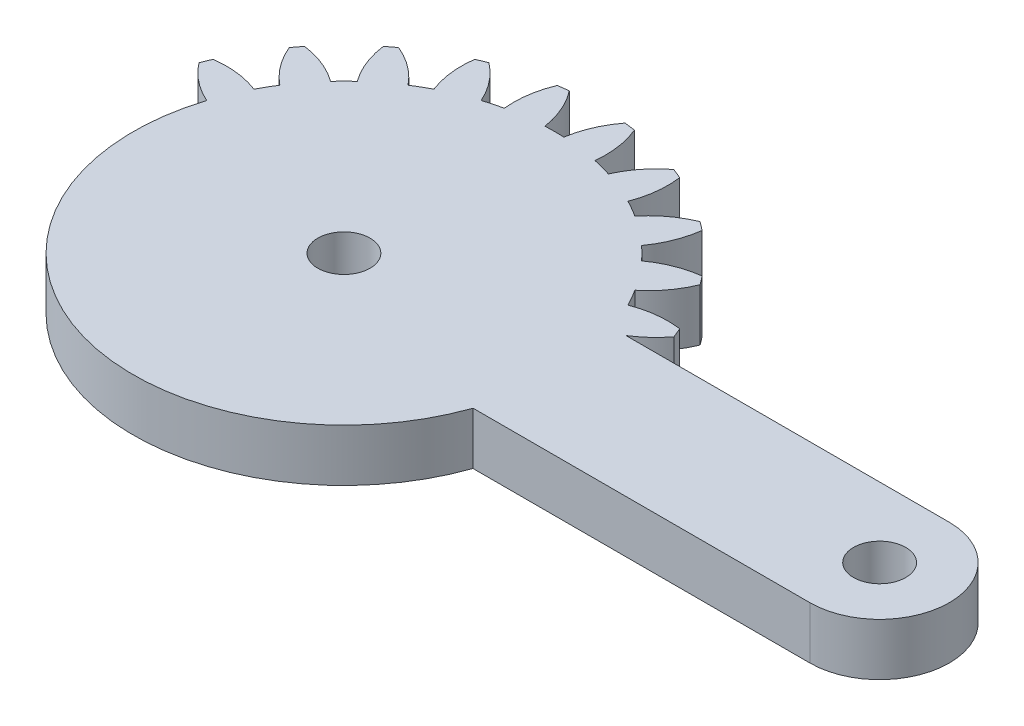
SolidWorks part; units mm, degrees
ref_plane "Front Plane" through (0, 0, 0) normal (0, 0, 1) x (1, 0, 0)
ref_plane "Top Plane" through (0, 0, 0) normal (0, 1, 0) x (1, 0, 0)
ref_plane "Right Plane" through (0, 0, 0) normal (1, 0, 0) x (0, 0, -1)
sketch "Sketch1" plane through (0, 0, 0) normal (0, 1, 0) x (1, 0, 0)
  line L0 (20.6437, 4) -> (2.0816, 4)
  line L1 (2.0816, -4) -> (20.6437, -4)
  arc A0 (2.0816, 4) -> (3.5217, 5.3071) centre (-0.7683, 8.5867) ccw
  arc A1 (3.5217, 5.3071) -> (3.2829, 5.8838) centre (-10.1063, 0) ccw
  arc A2 (3.2829, 5.8838) -> (0.6271, 5.5703) centre (2.5684, 0.5313) ccw
  arc A3 (0.6271, 5.5703) -> (0.0844, 6.5103) centre (-10.1063, 0) ccw
  arc A4 (0.0844, 6.5103) -> (1.6838, 8.6535) centre (-3.3089, 10.711) ccw
  arc A5 (1.6838, 8.6535) -> (1.3038, 9.1487) centre (-10.1063, 0) ccw
  arc A6 (1.3038, 9.1487) -> (-1.1803, 8.1585) centre (1.999, 3.7936) ccw
  arc A7 (-1.1803, 8.1585) -> (-1.9479, 8.926) centre (-10.1063, 0) ccw
  arc A8 (-1.9479, 8.926) -> (-0.9576, 11.4102) centre (-6.3127, 12.1053) ccw
  arc A9 (-0.9576, 11.4102) -> (-1.4528, 11.7901) centre (-10.1063, 0) ccw
  arc A10 (-1.4528, 11.7901) -> (-3.596, 10.1907) centre (0.6046, 6.7975) ccw
  arc A11 (-3.596, 10.1907) -> (-4.5361, 10.7334) centre (-10.1063, 0) ccw
  arc A12 (-4.5361, 10.7334) -> (-4.2225, 13.3892) centre (-9.5751, 12.6747) ccw
  arc A13 (-4.2225, 13.3892) -> (-4.7992, 13.6281) centre (-10.1063, 0) ccw
  arc A14 (-4.7992, 13.6281) -> (-6.4554, 11.5285) centre (-1.5196, 9.3381) ccw
  arc A15 (-6.4554, 11.5285) -> (-7.5039, 11.8094) centre (-10.1063, 0) ccw
  arc A16 (-7.5039, 11.8094) -> (-7.8884, 14.4558) centre (-12.8736, 12.3803) ccw
  arc A17 (-7.8884, 14.4558) -> (-8.5072, 14.5373) centre (-10.1063, 0) ccw
  arc A18 (-8.5072, 14.5373) -> (-9.5636, 12.0806) centre (-4.2291, 11.2423) ccw
  arc A19 (-9.5636, 12.0806) -> (-10.6491, 12.0806) centre (-10.1063, 0) ccw
  arc A20 (-10.6491, 12.0806) -> (-11.7054, 14.5373) centre (-15.9836, 11.2423) ccw
  arc A21 (-11.7054, 14.5373) -> (-12.3243, 14.4558) centre (-10.1063, 0) ccw
  arc A22 (-12.3243, 14.4558) -> (-12.7088, 11.8094) centre (-7.3391, 12.3803) ccw
  arc A23 (-12.7088, 11.8094) -> (-13.7573, 11.5285) centre (-10.1063, 0) ccw
  arc A24 (-13.7573, 11.5285) -> (-15.4135, 13.6281) centre (-18.6931, 9.3381) ccw
  arc A25 (-15.4135, 13.6281) -> (-15.9901, 13.3892) centre (-10.1063, 0) ccw
  arc A26 (-15.9901, 13.3892) -> (-15.6766, 10.7334) centre (-10.6376, 12.6747) ccw
  arc A27 (-15.6766, 10.7334) -> (-16.6166, 10.1907) centre (-10.1063, 0) ccw
  arc A28 (-16.6166, 10.1907) -> (-18.7599, 11.7901) centre (-20.8173, 6.7975) ccw
  arc A29 (-18.7599, 11.7901) -> (-19.255, 11.4102) centre (-10.1063, 0) ccw
  arc A30 (-19.255, 11.4102) -> (-18.2648, 8.926) centre (-13.9, 12.1053) ccw
  arc A31 (-18.2648, 8.926) -> (-19.0324, 8.1585) centre (-10.1063, 0) ccw
  arc A32 (-19.0324, 8.1585) -> (-21.5165, 9.1487) centre (-22.2117, 3.7936) ccw
  arc A33 (-21.5165, 9.1487) -> (-21.8965, 8.6535) centre (-10.1063, 0) ccw
  arc A34 (-21.8965, 8.6535) -> (-20.2971, 6.5103) centre (-16.9038, 10.711) ccw
  arc A35 (-20.2971, 6.5103) -> (-20.8398, 5.5703) centre (-10.1063, 0) ccw
  arc A36 (-20.8398, 5.5703) -> (-23.4956, 5.8838) centre (-22.7811, 0.5313) ccw
  arc A37 (-23.4956, 5.8838) -> (-23.7344, 5.3071) centre (-10.1063, 0) ccw
  arc A38 (-23.7344, 5.3071) -> (-21.6348, 3.6509) centre (-19.4444, 8.5867) ccw
  arc A39 (-21.6348, 3.6509) -> (-21.9157, 2.6025) centre (-10.1063, 0) ccw
  arc A40 (-21.9157, 2.6025) -> (-24.5622, 2.2179) centre (-22.4867, -2.7673) ccw
  arc A41 (-24.5622, 2.2179) -> (-24.6437, 1.5991) centre (-10.1063, 0) ccw
  arc A42 (-24.6437, 1.5991) -> (-22.1869, 0.5427) centre (-21.3486, 5.8773) ccw
  arc A43 (-22.1869, 0.5427) -> (-22.1869, -0.5427) centre (-10.1063, 0) ccw
  arc A44 (-22.1869, -0.5427) -> (-24.6437, -1.5991) centre (-21.3486, -5.8773) ccw
  arc A45 (-24.6437, -1.5991) -> (-24.5622, -2.2179) centre (-10.1063, 0) ccw
  arc A46 (-24.5622, -2.2179) -> (-21.9157, -2.6025) centre (-22.4867, 2.7673) ccw
  arc A47 (-21.9157, -2.6025) -> (-21.6348, -3.6509) centre (-10.1063, 0) ccw
  arc A48 (-21.6348, -3.6509) -> (-23.7344, -5.3071) centre (-19.4444, -8.5867) ccw
  arc A49 (-23.7344, -5.3071) -> (-23.4956, -5.8838) centre (-10.1063, 0) ccw
  arc A50 (-23.4956, -5.8838) -> (-20.8398, -5.5703) centre (-22.7811, -0.5313) ccw
  arc A51 (-20.8398, -5.5703) -> (-20.2971, -6.5103) centre (-10.1063, 0) ccw
  arc A52 (-20.2971, -6.5103) -> (-21.8965, -8.6535) centre (-16.9038, -10.711) ccw
  arc A53 (-21.8965, -8.6535) -> (-21.5165, -9.1487) centre (-10.1063, 0) ccw
  arc A54 (-21.5165, -9.1487) -> (-19.0324, -8.1585) centre (-22.2117, -3.7936) ccw
  arc A55 (-19.0324, -8.1585) -> (-18.2648, -8.926) centre (-10.1063, 0) ccw
  arc A56 (-18.2648, -8.926) -> (-19.255, -11.4102) centre (-13.9, -12.1053) ccw
  arc A57 (-19.255, -11.4102) -> (-18.7599, -11.7901) centre (-10.1063, 0) ccw
  arc A58 (-18.7599, -11.7901) -> (-16.6166, -10.1907) centre (-20.8173, -6.7975) ccw
  arc A59 (-16.6166, -10.1907) -> (-15.6766, -10.7334) centre (-10.1063, 0) ccw
  arc A60 (-15.6766, -10.7334) -> (-15.9901, -13.3892) centre (-10.6376, -12.6747) ccw
  arc A61 (-15.9901, -13.3892) -> (-15.4135, -13.6281) centre (-10.1063, 0) ccw
  arc A62 (-15.4135, -13.6281) -> (-13.7573, -11.5285) centre (-18.6931, -9.3381) ccw
  arc A63 (-13.7573, -11.5285) -> (-12.7088, -11.8094) centre (-10.1063, 0) ccw
  arc A64 (-12.7088, -11.8094) -> (-12.3243, -14.4558) centre (-7.3391, -12.3803) ccw
  arc A65 (-12.3243, -14.4558) -> (-11.7054, -14.5373) centre (-10.1063, 0) ccw
  arc A66 (-11.7054, -14.5373) -> (-10.6491, -12.0806) centre (-15.9836, -11.2423) ccw
  arc A67 (-10.6491, -12.0806) -> (-9.5636, -12.0806) centre (-10.1063, 0) ccw
  arc A68 (-9.5636, -12.0806) -> (-8.5072, -14.5373) centre (-4.2291, -11.2423) ccw
  arc A69 (-8.5072, -14.5373) -> (-7.8884, -14.4558) centre (-10.1063, 0) ccw
  arc A70 (-7.8884, -14.4558) -> (-7.5039, -11.8094) centre (-12.8736, -12.3803) ccw
  arc A71 (-7.5039, -11.8094) -> (-6.4554, -11.5285) centre (-10.1063, 0) ccw
  arc A72 (-6.4554, -11.5285) -> (-4.7992, -13.6281) centre (-1.5196, -9.3381) ccw
  arc A73 (-4.7992, -13.6281) -> (-4.2225, -13.3892) centre (-10.1063, 0) ccw
  arc A74 (-4.2225, -13.3892) -> (-4.5361, -10.7334) centre (-9.5751, -12.6747) ccw
  arc A75 (-4.5361, -10.7334) -> (-3.596, -10.1907) centre (-10.1063, 0) ccw
  arc A76 (-3.596, -10.1907) -> (-1.4528, -11.7901) centre (0.6046, -6.7975) ccw
  arc A77 (-1.4528, -11.7901) -> (-0.9576, -11.4102) centre (-10.1063, 0) ccw
  arc A78 (-0.9576, -11.4102) -> (-1.9479, -8.926) centre (-6.3127, -12.1053) ccw
  arc A79 (-1.9479, -8.926) -> (-1.1803, -8.1585) centre (-10.1063, 0) ccw
  arc A80 (-1.1803, -8.1585) -> (1.3038, -9.1487) centre (1.999, -3.7936) ccw
  arc A81 (1.3038, -9.1487) -> (1.6838, -8.6535) centre (-10.1063, 0) ccw
  arc A82 (1.6838, -8.6535) -> (0.0844, -6.5103) centre (-3.3089, -10.711) ccw
  arc A83 (0.0844, -6.5103) -> (0.6271, -5.5703) centre (-10.1063, 0) ccw
  arc A84 (0.6271, -5.5703) -> (3.2829, -5.8838) centre (2.5684, -0.5313) ccw
  arc A85 (3.2829, -5.8838) -> (3.5217, -5.3071) centre (-10.1063, 0) ccw
  arc A86 (3.5217, -5.3071) -> (2.0816, -4) centre (-0.7683, -8.5867) ccw
  arc A87 (20.6437, -4) -> (20.6437, 4) centre (20.6437, 0) ccw
  circle A88 centre (-10.1063, 0) radius 1.5
  circle A89 centre (20.6437, 0) radius 1.5
  dimension "D1" = 3
  dimension "D2" = 3
extrude "Boss-Extrude1" add sketch "Sketch1" along normal blind 3
sketch "Sketch2" plane through (0, 3, 0) normal (0, 1, 0) x (1, 0, 0)
  line L0 (2.0816, -4) -> (1.3057, -4)
  line L2 (20.6437, 4) -> (2.0816, 4)
  line L3 (2.0816, -4) -> (20.6437, -4)
  line L4 (20.6437, 4) -> (2.0816, 4)
  line L5 (2.0816, -4) -> (20.6437, -4)
  circle A0 centre (-10.1063, 0) radius 12.0927
  arc A88 (20.6437, -4) -> (20.6437, 4) centre (20.6437, 0) ccw
  arc A89 (2.0816, 4) -> (3.5217, 5.3071) centre (-0.7683, 8.5867) ccw
  arc A90 (3.5217, 5.3071) -> (3.2829, 5.8838) centre (-10.1063, 0) ccw
  arc A91 (3.2829, 5.8838) -> (0.6271, 5.5703) centre (2.5684, 0.5313) ccw
  arc A92 (0.6271, 5.5703) -> (0.0844, 6.5103) centre (-10.1063, 0) ccw
  arc A93 (0.0844, 6.5103) -> (1.6838, 8.6535) centre (-3.3089, 10.711) ccw
  arc A94 (1.6838, 8.6535) -> (1.3038, 9.1487) centre (-10.1063, 0) ccw
  arc A95 (1.3038, 9.1487) -> (-1.1803, 8.1585) centre (1.999, 3.7936) ccw
  arc A96 (-1.1803, 8.1585) -> (-1.9479, 8.926) centre (-10.1063, 0) ccw
  arc A97 (-1.9479, 8.926) -> (-0.9576, 11.4102) centre (-6.3127, 12.1053) ccw
  arc A98 (-0.9576, 11.4102) -> (-1.4528, 11.7901) centre (-10.1063, 0) ccw
  arc A99 (-1.4528, 11.7901) -> (-3.596, 10.1907) centre (0.6046, 6.7975) ccw
  arc A100 (-3.596, 10.1907) -> (-4.5361, 10.7334) centre (-10.1063, 0) ccw
  arc A101 (-4.5361, 10.7334) -> (-4.2225, 13.3892) centre (-9.5751, 12.6747) ccw
  arc A102 (-4.2225, 13.3892) -> (-4.7992, 13.6281) centre (-10.1063, 0) ccw
  arc A103 (-4.7992, 13.6281) -> (-6.4554, 11.5285) centre (-1.5196, 9.3381) ccw
  arc A104 (-6.4554, 11.5285) -> (-7.5039, 11.8094) centre (-10.1063, 0) ccw
  arc A105 (-7.5039, 11.8094) -> (-7.8884, 14.4558) centre (-12.8736, 12.3803) ccw
  arc A106 (-7.8884, 14.4558) -> (-8.5072, 14.5373) centre (-10.1063, 0) ccw
  arc A107 (-8.5072, 14.5373) -> (-9.5636, 12.0806) centre (-4.2291, 11.2423) ccw
  arc A108 (-9.5636, 12.0806) -> (-10.6491, 12.0806) centre (-10.1063, 0) ccw
  arc A109 (-10.6491, 12.0806) -> (-11.7054, 14.5373) centre (-15.9836, 11.2423) ccw
  arc A110 (-11.7054, 14.5373) -> (-12.3243, 14.4558) centre (-10.1063, 0) ccw
  arc A111 (-12.3243, 14.4558) -> (-12.7088, 11.8094) centre (-7.3391, 12.3803) ccw
  arc A112 (-12.7088, 11.8094) -> (-13.7573, 11.5285) centre (-10.1063, 0) ccw
  arc A113 (-13.7573, 11.5285) -> (-15.4135, 13.6281) centre (-18.6931, 9.3381) ccw
  arc A114 (-15.4135, 13.6281) -> (-15.9901, 13.3892) centre (-10.1063, 0) ccw
  arc A115 (-15.9901, 13.3892) -> (-15.6766, 10.7334) centre (-10.6376, 12.6747) ccw
  arc A116 (-15.6766, 10.7334) -> (-16.6166, 10.1907) centre (-10.1063, 0) ccw
  arc A117 (-16.6166, 10.1907) -> (-18.7599, 11.7901) centre (-20.8173, 6.7975) ccw
  arc A118 (-18.7599, 11.7901) -> (-19.255, 11.4102) centre (-10.1063, 0) ccw
  arc A119 (-19.255, 11.4102) -> (-18.2648, 8.926) centre (-13.9, 12.1053) ccw
  arc A120 (-18.2648, 8.926) -> (-19.0324, 8.1585) centre (-10.1063, 0) ccw
  arc A121 (-19.0324, 8.1585) -> (-21.5165, 9.1487) centre (-22.2117, 3.7936) ccw
  arc A122 (-21.5165, 9.1487) -> (-21.8965, 8.6535) centre (-10.1063, 0) ccw
  arc A123 (-21.8965, 8.6535) -> (-20.2971, 6.5103) centre (-16.9038, 10.711) ccw
  arc A124 (-20.2971, 6.5103) -> (-20.8398, 5.5703) centre (-10.1063, 0) ccw
  arc A125 (-20.8398, 5.5703) -> (-23.4956, 5.8838) centre (-22.7811, 0.5313) ccw
  arc A126 (-23.4956, 5.8838) -> (-23.7344, 5.3071) centre (-10.1063, 0) ccw
  arc A127 (-23.7344, 5.3071) -> (-21.6348, 3.6509) centre (-19.4444, 8.5867) ccw
  arc A128 (-21.6348, 3.6509) -> (-21.9157, 2.6025) centre (-10.1063, 0) ccw
  arc A129 (-21.9157, 2.6025) -> (-24.5622, 2.2179) centre (-22.4867, -2.7673) ccw
  arc A130 (-24.5622, 2.2179) -> (-24.6437, 1.5991) centre (-10.1063, 0) ccw
  arc A131 (-24.6437, 1.5991) -> (-22.1869, 0.5427) centre (-21.3486, 5.8773) ccw
  arc A132 (-22.1869, 0.5427) -> (-22.1869, -0.5427) centre (-10.1063, 0) ccw
  arc A133 (-22.1869, -0.5427) -> (-24.6437, -1.5991) centre (-21.3486, -5.8773) ccw
  arc A134 (-24.6437, -1.5991) -> (-24.5622, -2.2179) centre (-10.1063, 0) ccw
  arc A135 (-24.5622, -2.2179) -> (-21.9157, -2.6025) centre (-22.4867, 2.7673) ccw
  arc A136 (-21.9157, -2.6025) -> (-21.6348, -3.6509) centre (-10.1063, 0) ccw
  arc A137 (-21.6348, -3.6509) -> (-23.7344, -5.3071) centre (-19.4444, -8.5867) ccw
  arc A138 (-23.7344, -5.3071) -> (-23.4956, -5.8838) centre (-10.1063, 0) ccw
  arc A139 (-23.4956, -5.8838) -> (-20.8398, -5.5703) centre (-22.7811, -0.5313) ccw
  arc A140 (-20.8398, -5.5703) -> (-20.2971, -6.5103) centre (-10.1063, 0) ccw
  arc A141 (-20.2971, -6.5103) -> (-21.8965, -8.6535) centre (-16.9038, -10.711) ccw
  arc A142 (-21.8965, -8.6535) -> (-21.5165, -9.1487) centre (-10.1063, 0) ccw
  arc A143 (-21.5165, -9.1487) -> (-19.0324, -8.1585) centre (-22.2117, -3.7936) ccw
  arc A144 (-19.0324, -8.1585) -> (-18.2648, -8.926) centre (-10.1063, 0) ccw
  arc A145 (-18.2648, -8.926) -> (-19.255, -11.4102) centre (-13.9, -12.1053) ccw
  arc A146 (-19.255, -11.4102) -> (-18.7599, -11.7901) centre (-10.1063, 0) ccw
  arc A147 (-18.7599, -11.7901) -> (-16.6166, -10.1907) centre (-20.8173, -6.7975) ccw
  arc A148 (-16.6166, -10.1907) -> (-15.6766, -10.7334) centre (-10.1063, 0) ccw
  arc A149 (-15.6766, -10.7334) -> (-15.9901, -13.3892) centre (-10.6376, -12.6747) ccw
  arc A150 (-15.9901, -13.3892) -> (-15.4135, -13.6281) centre (-10.1063, 0) ccw
  arc A151 (-15.4135, -13.6281) -> (-13.7573, -11.5285) centre (-18.6931, -9.3381) ccw
  arc A152 (-13.7573, -11.5285) -> (-12.7088, -11.8094) centre (-10.1063, 0) ccw
  arc A153 (-12.7088, -11.8094) -> (-12.3243, -14.4558) centre (-7.3391, -12.3803) ccw
  arc A154 (-12.3243, -14.4558) -> (-11.7054, -14.5373) centre (-10.1063, 0) ccw
  arc A155 (-11.7054, -14.5373) -> (-10.6491, -12.0806) centre (-15.9836, -11.2423) ccw
  arc A156 (-10.6491, -12.0806) -> (-9.5636, -12.0806) centre (-10.1063, 0) ccw
  arc A157 (-9.5636, -12.0806) -> (-8.5072, -14.5373) centre (-4.2291, -11.2423) ccw
  arc A158 (-8.5072, -14.5373) -> (-7.8884, -14.4558) centre (-10.1063, 0) ccw
  arc A159 (-7.8884, -14.4558) -> (-7.5039, -11.8094) centre (-12.8736, -12.3803) ccw
  arc A160 (-7.5039, -11.8094) -> (-6.4554, -11.5285) centre (-10.1063, 0) ccw
  arc A161 (-6.4554, -11.5285) -> (-4.7992, -13.6281) centre (-1.5196, -9.3381) ccw
  arc A162 (-4.7992, -13.6281) -> (-4.2225, -13.3892) centre (-10.1063, 0) ccw
  arc A163 (-4.2225, -13.3892) -> (-4.5361, -10.7334) centre (-9.5751, -12.6747) ccw
  arc A164 (-4.5361, -10.7334) -> (-3.596, -10.1907) centre (-10.1063, 0) ccw
  arc A165 (-3.596, -10.1907) -> (-1.4528, -11.7901) centre (0.6046, -6.7975) ccw
  arc A166 (-1.4528, -11.7901) -> (-0.9576, -11.4102) centre (-10.1063, 0) ccw
  arc A167 (-0.9576, -11.4102) -> (-1.9479, -8.926) centre (-6.3127, -12.1053) ccw
  arc A168 (-1.9479, -8.926) -> (-1.1803, -8.1585) centre (-10.1063, 0) ccw
  arc A169 (-1.1803, -8.1585) -> (1.3038, -9.1487) centre (1.999, -3.7936) ccw
  arc A170 (1.3038, -9.1487) -> (1.6838, -8.6535) centre (-10.1063, 0) ccw
  arc A171 (1.6838, -8.6535) -> (0.0844, -6.5103) centre (-3.3089, -10.711) ccw
  arc A172 (0.0844, -6.5103) -> (0.6271, -5.5703) centre (-10.1063, 0) ccw
  arc A173 (0.6271, -5.5703) -> (3.2829, -5.8838) centre (2.5684, -0.5313) ccw
  arc A174 (3.2829, -5.8838) -> (3.5217, -5.3071) centre (-10.1063, 0) ccw
  arc A175 (3.5217, -5.3071) -> (2.0816, -4) centre (-0.7683, -8.5867) ccw
  arc A176 (20.6437, -4) -> (20.6437, 4) centre (20.6437, 0) ccw
  arc A177 (2.0816, 4) -> (3.5217, 5.3071) centre (-0.7683, 8.5867) ccw
  arc A178 (3.5217, 5.3071) -> (3.2829, 5.8838) centre (-10.1063, 0) ccw
  arc A179 (3.2829, 5.8838) -> (0.6271, 5.5703) centre (2.5684, 0.5313) ccw
  arc A180 (0.6271, 5.5703) -> (0.0844, 6.5103) centre (-10.1063, 0) ccw
  arc A181 (0.0844, 6.5103) -> (1.6838, 8.6535) centre (-3.3089, 10.711) ccw
  arc A182 (1.6838, 8.6535) -> (1.3038, 9.1487) centre (-10.1063, 0) ccw
  arc A183 (1.3038, 9.1487) -> (-1.1803, 8.1585) centre (1.999, 3.7936) ccw
  arc A184 (-1.1803, 8.1585) -> (-1.9479, 8.926) centre (-10.1063, 0) ccw
  arc A185 (-1.9479, 8.926) -> (-0.9576, 11.4102) centre (-6.3127, 12.1053) ccw
  arc A186 (-0.9576, 11.4102) -> (-1.4528, 11.7901) centre (-10.1063, 0) ccw
  arc A187 (-1.4528, 11.7901) -> (-3.596, 10.1907) centre (0.6046, 6.7975) ccw
  arc A188 (-3.596, 10.1907) -> (-4.5361, 10.7334) centre (-10.1063, 0) ccw
  arc A189 (-4.5361, 10.7334) -> (-4.2225, 13.3892) centre (-9.5751, 12.6747) ccw
  arc A190 (-4.2225, 13.3892) -> (-4.7992, 13.6281) centre (-10.1063, 0) ccw
  arc A191 (-4.7992, 13.6281) -> (-6.4554, 11.5285) centre (-1.5196, 9.3381) ccw
  arc A192 (-6.4554, 11.5285) -> (-7.5039, 11.8094) centre (-10.1063, 0) ccw
  arc A193 (-7.5039, 11.8094) -> (-7.8884, 14.4558) centre (-12.8736, 12.3803) ccw
  arc A194 (-7.8884, 14.4558) -> (-8.5072, 14.5373) centre (-10.1063, 0) ccw
  arc A195 (-8.5072, 14.5373) -> (-9.5636, 12.0806) centre (-4.2291, 11.2423) ccw
  arc A196 (-9.5636, 12.0806) -> (-10.6491, 12.0806) centre (-10.1063, 0) ccw
  arc A197 (-10.6491, 12.0806) -> (-11.7054, 14.5373) centre (-15.9836, 11.2423) ccw
  arc A198 (-11.7054, 14.5373) -> (-12.3243, 14.4558) centre (-10.1063, 0) ccw
  arc A199 (-12.3243, 14.4558) -> (-12.7088, 11.8094) centre (-7.3391, 12.3803) ccw
  arc A200 (-12.7088, 11.8094) -> (-13.7573, 11.5285) centre (-10.1063, 0) ccw
  arc A201 (-13.7573, 11.5285) -> (-15.4135, 13.6281) centre (-18.6931, 9.3381) ccw
  arc A202 (-15.4135, 13.6281) -> (-15.9901, 13.3892) centre (-10.1063, 0) ccw
  arc A203 (-15.9901, 13.3892) -> (-15.6766, 10.7334) centre (-10.6376, 12.6747) ccw
  arc A204 (-15.6766, 10.7334) -> (-16.6166, 10.1907) centre (-10.1063, 0) ccw
  arc A205 (-16.6166, 10.1907) -> (-18.7599, 11.7901) centre (-20.8173, 6.7975) ccw
  arc A206 (-18.7599, 11.7901) -> (-19.255, 11.4102) centre (-10.1063, 0) ccw
  arc A207 (-19.255, 11.4102) -> (-18.2648, 8.926) centre (-13.9, 12.1053) ccw
  arc A208 (-18.2648, 8.926) -> (-19.0324, 8.1585) centre (-10.1063, 0) ccw
  arc A209 (-19.0324, 8.1585) -> (-21.5165, 9.1487) centre (-22.2117, 3.7936) ccw
  arc A210 (-21.5165, 9.1487) -> (-21.8965, 8.6535) centre (-10.1063, 0) ccw
  arc A211 (-21.8965, 8.6535) -> (-20.2971, 6.5103) centre (-16.9038, 10.711) ccw
  arc A212 (-20.2971, 6.5103) -> (-20.8398, 5.5703) centre (-10.1063, 0) ccw
  arc A213 (-20.8398, 5.5703) -> (-23.4956, 5.8838) centre (-22.7811, 0.5313) ccw
  arc A214 (-23.4956, 5.8838) -> (-23.7344, 5.3071) centre (-10.1063, 0) ccw
  arc A215 (-23.7344, 5.3071) -> (-21.6348, 3.6509) centre (-19.4444, 8.5867) ccw
  arc A216 (-21.6348, 3.6509) -> (-21.9157, 2.6025) centre (-10.1063, 0) ccw
  arc A217 (-21.9157, 2.6025) -> (-24.5622, 2.2179) centre (-22.4867, -2.7673) ccw
  arc A218 (-24.5622, 2.2179) -> (-24.6437, 1.5991) centre (-10.1063, 0) ccw
  arc A219 (-24.6437, 1.5991) -> (-22.1869, 0.5427) centre (-21.3486, 5.8773) ccw
  arc A220 (-22.1869, 0.5427) -> (-22.1869, -0.5427) centre (-10.1063, 0) ccw
  arc A221 (-22.1869, -0.5427) -> (-24.6437, -1.5991) centre (-21.3486, -5.8773) ccw
  arc A222 (-24.6437, -1.5991) -> (-24.5622, -2.2179) centre (-10.1063, 0) ccw
  arc A223 (-24.5622, -2.2179) -> (-21.9157, -2.6025) centre (-22.4867, 2.7673) ccw
  arc A224 (-21.9157, -2.6025) -> (-21.6348, -3.6509) centre (-10.1063, 0) ccw
  arc A225 (-21.6348, -3.6509) -> (-23.7344, -5.3071) centre (-19.4444, -8.5867) ccw
  arc A226 (-23.7344, -5.3071) -> (-23.4956, -5.8838) centre (-10.1063, 0) ccw
  arc A227 (-23.4956, -5.8838) -> (-20.8398, -5.5703) centre (-22.7811, -0.5313) ccw
  arc A228 (-20.8398, -5.5703) -> (-20.2971, -6.5103) centre (-10.1063, 0) ccw
  arc A229 (-20.2971, -6.5103) -> (-21.8965, -8.6535) centre (-16.9038, -10.711) ccw
  arc A230 (-21.8965, -8.6535) -> (-21.5165, -9.1487) centre (-10.1063, 0) ccw
  arc A231 (-21.5165, -9.1487) -> (-19.0324, -8.1585) centre (-22.2117, -3.7936) ccw
  arc A232 (-19.0324, -8.1585) -> (-18.2648, -8.926) centre (-10.1063, 0) ccw
  arc A233 (-18.2648, -8.926) -> (-19.255, -11.4102) centre (-13.9, -12.1053) ccw
  arc A234 (-19.255, -11.4102) -> (-18.7599, -11.7901) centre (-10.1063, 0) ccw
  arc A235 (-18.7599, -11.7901) -> (-16.6166, -10.1907) centre (-20.8173, -6.7975) ccw
  arc A236 (-16.6166, -10.1907) -> (-15.6766, -10.7334) centre (-10.1063, 0) ccw
  arc A237 (-15.6766, -10.7334) -> (-15.9901, -13.3892) centre (-10.6376, -12.6747) ccw
  arc A238 (-15.9901, -13.3892) -> (-15.4135, -13.6281) centre (-10.1063, 0) ccw
  arc A239 (-15.4135, -13.6281) -> (-13.7573, -11.5285) centre (-18.6931, -9.3381) ccw
  arc A240 (-13.7573, -11.5285) -> (-12.7088, -11.8094) centre (-10.1063, 0) ccw
  arc A241 (-12.7088, -11.8094) -> (-12.3243, -14.4558) centre (-7.3391, -12.3803) ccw
  arc A242 (-12.3243, -14.4558) -> (-11.7054, -14.5373) centre (-10.1063, 0) ccw
  arc A243 (-11.7054, -14.5373) -> (-10.6491, -12.0806) centre (-15.9836, -11.2423) ccw
  arc A244 (-10.6491, -12.0806) -> (-9.5636, -12.0806) centre (-10.1063, 0) ccw
  arc A245 (-9.5636, -12.0806) -> (-8.5072, -14.5373) centre (-4.2291, -11.2423) ccw
  arc A246 (-8.5072, -14.5373) -> (-7.8884, -14.4558) centre (-10.1063, 0) ccw
  arc A247 (-7.8884, -14.4558) -> (-7.5039, -11.8094) centre (-12.8736, -12.3803) ccw
  arc A248 (-7.5039, -11.8094) -> (-6.4554, -11.5285) centre (-10.1063, 0) ccw
  arc A249 (-6.4554, -11.5285) -> (-4.7992, -13.6281) centre (-1.5196, -9.3381) ccw
  arc A250 (-4.7992, -13.6281) -> (-4.2225, -13.3892) centre (-10.1063, 0) ccw
  arc A251 (-4.2225, -13.3892) -> (-4.5361, -10.7334) centre (-9.5751, -12.6747) ccw
  arc A252 (-4.5361, -10.7334) -> (-3.596, -10.1907) centre (-10.1063, 0) ccw
  arc A253 (-3.596, -10.1907) -> (-1.4528, -11.7901) centre (0.6046, -6.7975) ccw
  arc A254 (-1.4528, -11.7901) -> (-0.9576, -11.4102) centre (-10.1063, 0) ccw
  arc A255 (-0.9576, -11.4102) -> (-1.9479, -8.926) centre (-6.3127, -12.1053) ccw
  arc A256 (-1.9479, -8.926) -> (-1.1803, -8.1585) centre (-10.1063, 0) ccw
  arc A257 (-1.1803, -8.1585) -> (1.3038, -9.1487) centre (1.999, -3.7936) ccw
  arc A258 (1.3038, -9.1487) -> (1.6838, -8.6535) centre (-10.1063, 0) ccw
  arc A259 (1.6838, -8.6535) -> (0.0844, -6.5103) centre (-3.3089, -10.711) ccw
  arc A260 (0.0844, -6.5103) -> (0.6271, -5.5703) centre (-10.1063, 0) ccw
  arc A261 (0.6271, -5.5703) -> (3.2829, -5.8838) centre (2.5684, -0.5313) ccw
  arc A262 (3.2829, -5.8838) -> (3.5217, -5.3071) centre (-10.1063, 0) ccw
  arc A263 (3.5217, -5.3071) -> (2.0816, -4) centre (-0.7683, -8.5867) ccw
  dimension "D1" = 0
extrude "Cut-Extrude1" cut sketch "Sketch2" against normal blind 10 contours A222 A223 A0 A221 | A226 A227 A0 A225 | A230 A231 A0 A229 | A234 A235 A0 A233 | A238 A239 A0 A237 | A242 A243 A0 A241 | A246 A247 A0 A245 | A250 A251 A0 A249 | A254 A255 A0 A253 | A258 A259 A0 A257 | A262 A263 L0 A0 A261 | A218 A219 A0 A217
